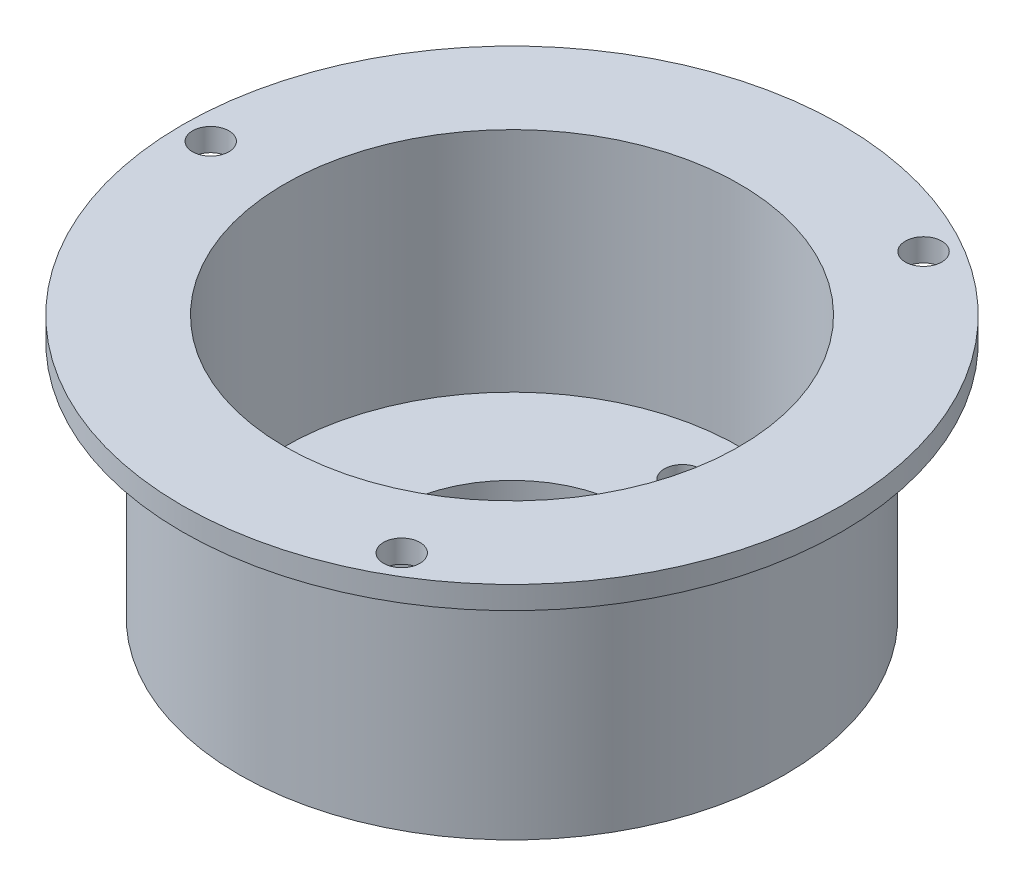
SolidWorks part; units mm, degrees
ref_plane "Front Plane" through (0, 0, 0) normal (0, 0, 1) x (1, 0, 0)
ref_plane "Top Plane" through (0, 0, 0) normal (0, 1, 0) x (1, 0, 0)
ref_plane "Right Plane" through (0, 0, 0) normal (1, 0, 0) x (0, 0, -1)
sketch "Sketch1" plane through (0, 0, 0) normal (0, 1, 0) x (1, 0, 0)
  circle A0 centre (0, 0) radius 24
  circle A1 centre (0, 0) radius 20
  dimension "D1" = 48
  dimension "D2" = 40
extrude "Boss-Extrude1" add sketch "Sketch1" along normal blind 18
sketch "Sketch2" plane through (0, 0, 0) normal (0, 1, 0) x (1, 0, 0)
  circle A0 centre (0, 0) radius 24
  circle A1 centre (0, 0) radius 10.5
  circle A2 centre (0, 0) radius 15 construction
  circle A3 centre (0, 15) radius 1.6
  circle A4 centre (12.9904, -7.5) radius 1.6
  circle A5 centre (-12.9904, -7.5) radius 1.6
  dimension "D1" = 21
  dimension "D2" = 3.2
  dimension "D3" = 3
extrude "Boss-Extrude2" add sketch "Sketch2" against normal blind 3
sketch "Sketch3" plane through (0, 18, 0) normal (0, 1, 0) x (1, 0, 0)
  line L0 (-29, 0) -> (-24, 0) construction
  circle A0 centre (0, 0) radius 20
  circle A1 centre (0, 0) radius 29
  circle A2 centre (0, 0) radius 24 construction
  circle A3 centre (-26.5, 0) radius 1.6
  circle A4 centre (13.25, 22.9497) radius 1.6
  circle A5 centre (13.25, -22.9497) radius 1.6
  dimension "D1" = 5
  dimension "D2" = 3.2
  dimension "D3" = 3
extrude "Boss-Extrude3" add sketch "Sketch3" along normal blind 2
